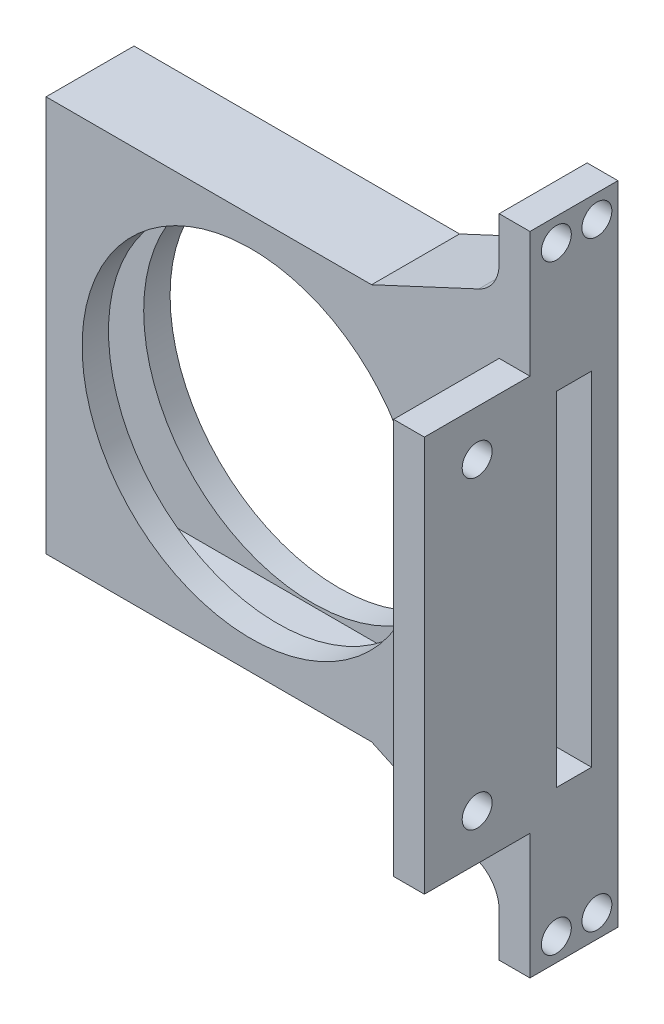
SolidWorks part; units mm, degrees
ref_plane "前视基准面" through (0, 0, 0) normal (0, 0, 1) x (1, 0, 0)
ref_plane "上视基准面" through (0, 0, 0) normal (0, 1, 0) x (1, 0, 0)
ref_plane "右视基准面" through (0, 0, 0) normal (1, 0, 0) x (0, 0, -1)
sketch "草图1" plane through (0, 0, 0) normal (0, 0, 1) x (1, 0, 0)
  line L0 (25.9619, 0) -> (-25.9619, 0) construction
  line L1 (-27.5, 22.5) -> (27.5, 22.5)
  line L2 (-27.5, 22.5) -> (-27.5, -22.5)
  line L3 (-27.5, -22.5) -> (27.5, -22.5)
  line L4 (27.5, 22.5) -> (27.5, -22.5)
  line L5 (-27.5, 22.5) -> (27.5, -22.5) construction
  line L6 (-27.5, -22.5) -> (27.5, 22.5) construction
  point P0 (0, 0)
  point P9 (0, 0)
  dimension "D1" = 45
  dimension "D2" = 55
extrude "凸台-拉伸1" add sketch "草图1" along normal blind 3
sketch "草图2" plane through (0, 0, 3) normal (0, 0, 1) x (1, 0, 0)
  line L0 (27.5, -22.5) -> (27.5, 22.5)
  line L1 (27.5, 22.5) -> (24, 22.5)
  line L2 (27.5, 22.5) -> (-27.5, 22.5) construction
  line L3 (24, 22.5) -> (24, -22.5)
  line L4 (-27.5, -22.5) -> (27.5, -22.5) construction
  line L5 (24, -22.5) -> (27.5, -22.5)
extrude "凸台-拉伸2" add sketch "草图2" along normal blind 12
sketch "草图3" plane through (24, 0, 0) normal (-1, 0, 0) x (0, 0, 1)
  line L0 (3, 22.5) -> (3, -22.5) construction
  circle A0 centre (9, -17.3) radius 1.7
  circle A1 centre (9, 17.3) radius 1.7
  dimension "D1" = 6
  dimension "D3" = 17.3
  dimension "D2" = 6
  dimension "D4" = 17.3
extrude "切除-拉伸1" cut sketch "草图3" against normal through all
sketch "草图5" plane through (0, 0, 0) normal (0, 0, 1) x (1, 0, 0)
  line L0 (27.5, -22.5) -> (9.5, -22.5)
  line L1 (-27.5, -22.5) -> (24, -22.5) construction
  line L2 (9.5, -22.5) -> (21.6892, -28.1789)
  line L5 (27.5, -36.7445) -> (24, -36.7445)
  line L6 (24, -36.7445) -> (24, -31.8047)
  line L7 (27.5, -36.7445) -> (27.5, -22.5)
  arc A0 (24, -31.8047) -> (21.6892, -28.1789) centre (20, -31.8047) ccw
  dimension "D1" = 4
extrude "凸台-拉伸3" add sketch "草图5" along normal blind 3 and the other way blind 7
sketch "草图6" plane through (24, 0, 0) normal (-1, 0, 0) x (0, 0, 1)
  circle A0 centre (0, -34.1294) radius 1.7
  circle A1 centre (-4.6079, -34.1294) radius 1.7
  dimension "D1" = 0
extrude "切除-拉伸2" cut sketch "草图6" against normal through all
mirror "镜向3" about plane through (0, 0, 0) normal (0, 1, 0) of "凸台-拉伸3", "切除-拉伸2"
sketch "草图7" plane through (0, 0, 3) normal (0, 0, 1) x (1, 0, 0)
  circle A2 centre (-4.205, 0) radius 19.2
extrude "切除-拉伸3" cut sketch "草图7" along direction (0, 0, 1) on the side against the normal through all and the other way through all
ref_plane "基准面1" through (0, -22.5, 0) normal (0, -1, 0) x (-1, 0, 0)
ref_plane "基准面2" through (0, 0, -2) normal (0, 0, 1) x (1, 0, 0)
mirror "镜向6" about plane through (0, 0, -2) normal (0, 0, 1) of "切除-拉伸3", "凸台-拉伸1"
sketch "草图10" plane through (0, -22.5, 0) normal (0, -1, 0) x (-1, 0, 0)
  line L0 (27.5, 4) -> (27.5, 0)
  line L1 (27.5, -3) -> (27.5, 0) construction
  line L2 (27.5, 0) -> (-27.5, 0)
  line L3 (-27.5, 0) -> (-27.5, 4)
  line L4 (-27.5, 4) -> (27.5, 4)
extrude "凸台-拉伸9" add sketch "草图10" against normal blind 3
mirror "镜向7" about plane through (0, 0, 0) normal (0, 1, 0) of "凸台-拉伸9"
